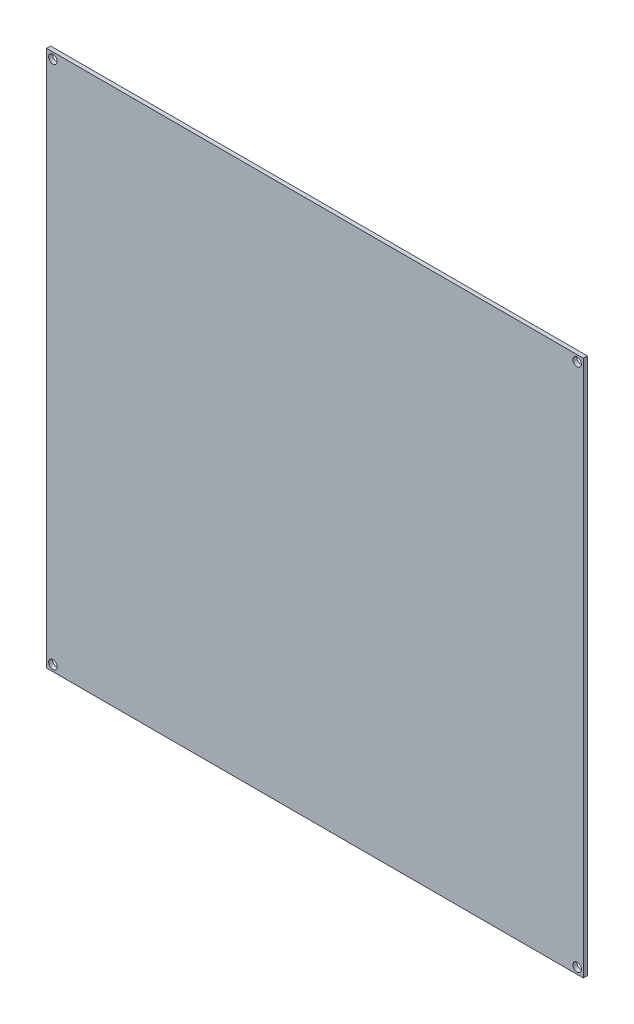
SolidWorks part; units mm, degrees
ref_plane "Front" through (0, 0, 0) normal (0, 0, 1) x (1, 0, 0)
ref_plane "Top" through (0, 0, 0) normal (0, 1, 0) x (1, 0, 0)
ref_plane "Right" through (0, 0, 0) normal (1, 0, 0) x (0, 0, -1)
ref_plane "Plane1" through (0, 0, -0.8) normal (0, 0, -1) x (-1, 0, 0)
sketch "Sketch1" plane through (0, 0, -0.8) normal (0, 0, -1) x (-1, 0, 0)
  line L36 (57, 225) -> (-157, 225)
  line L37 (-157, 225) -> (-157, 11)
  line L38 (-157, 11) -> (57, 11)
  line L39 (57, 11) -> (57, 225)
  dimension "D15" = 214
  dimension "D30" = 214
extrude "Boss-Extrude1" add sketch "Sketch1" against normal blind 1.6
sketch "Sketch2" plane through (0, 0, 0.8) normal (0, 0, 1) x (1, 0, 0)
  line L0 (-57, 11) -> (-57, 225) construction
  line L1 (-57, 225) -> (157, 225) construction
  line L2 (-54.5, 222.5) -> (166.8164, 222.5) construction
  line L3 (-54.5, 222.5) -> (-54.5, 8.2162) construction
  line L4 (-54.5, 13.5) -> (169.9842, 13.5) construction
  circle A0 centre (154.5, 13.5) radius 1.7
  circle A2 centre (-54.5, 222.5) radius 1.7
  circle A3 centre (154.5, 222.5) radius 1.7
  circle A4 centre (-54.5, 13.5) radius 1.7
  dimension "D1" = 209
  dimension "D2" = 209
  dimension "D3" = 209
  dimension "D4" = 2.5
  dimension "D5" = 2.5
extrude "Cut-Extrude1" cut sketch "Sketch2" against normal through all
